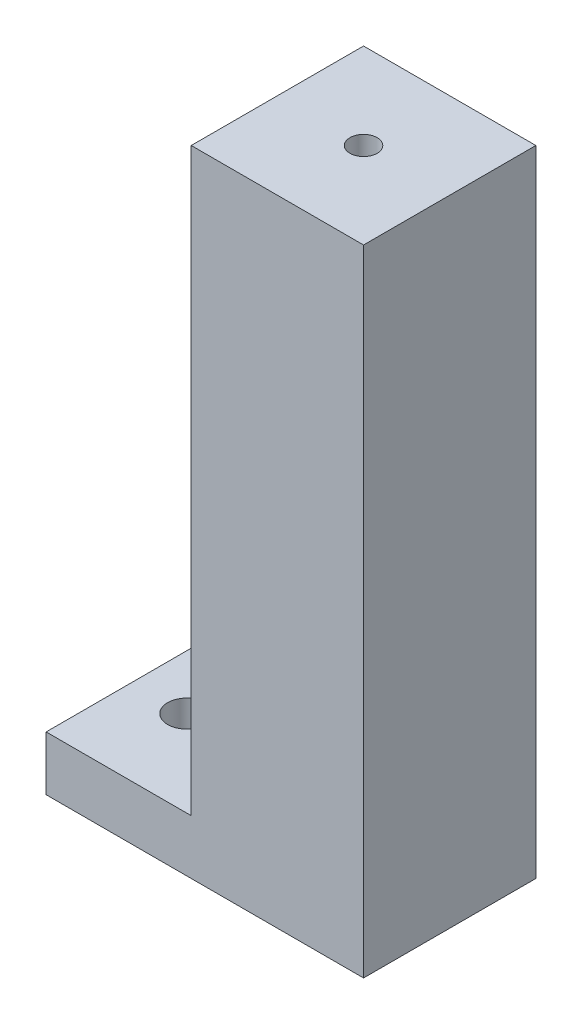
SolidWorks part; units mm, degrees
ref_plane "前视基准面" through (0, 0, 0) normal (0, 0, 1) x (1, 0, 0)
ref_plane "上视基准面" through (0, 0, 0) normal (0, 1, 0) x (1, 0, 0)
ref_plane "右视基准面" through (0, 0, 0) normal (1, 0, 0) x (0, 0, -1)
other "Configuration Table"
sketch "草图1" plane through (0, 0, 0) normal (0, 1, 0) x (1, 0, 0)
  line L0 (-16, 0) -> (0, 0) construction
  line L1 (-17.5, 9.5) -> (17.5, 9.5)
  line L2 (-17.5, 9.5) -> (-17.5, -9.5)
  line L3 (-17.5, -9.5) -> (17.5, -9.5)
  line L4 (17.5, 9.5) -> (17.5, -9.5)
  line L5 (-17.5, 9.5) -> (17.5, -9.5) construction
  line L6 (-17.5, -9.5) -> (17.5, 9.5) construction
  circle A0 centre (-11.5, 0) radius 2.1
  point P0 (0, 0)
  dimension "D4" = 4.2
  dimension "D1" = 19
  dimension "D2" = 35
  dimension "D3" = 6
extrude "凸台-拉伸1" add sketch "草图1" along normal blind 6
sketch "草图2" plane through (0, 6, 0) normal (0, 1, 0) x (1, 0, 0)
  line L0 (-17.5, -9.5) -> (17.5, -9.5) construction
  line L1 (-1.5, -9.5) -> (17.5, -9.5)
  line L2 (-1.5, -9.5) -> (-1.5, 9.5)
  line L3 (-1.5, 9.5) -> (17.5, 9.5)
  line L4 (17.5, -9.5) -> (17.5, 9.5)
  line L5 (-1.5, -9.5) -> (17.5, 9.5) construction
  line L6 (-1.5, 9.5) -> (17.5, -9.5) construction
  point P0 (8, 0)
  dimension "D1" = 19
extrude "凸台-拉伸2" add sketch "草图2" along normal up to surface (64 mm away)
sketch "草图4" plane through (0, 70, 0) normal (0, 1, 0) x (1, 0, 0)
  line L0 (8, 9.5) -> (8, -9.5) construction
  line L1 (17.5, 9.5) -> (-1.5, 9.5) construction
  line L2 (-1.5, -9.5) -> (17.5, -9.5) construction
  circle A0 centre (8, 0) radius 1.5
  dimension "D1" = 3
extrude "切除-拉伸1" cut sketch "草图4" against normal blind 10
